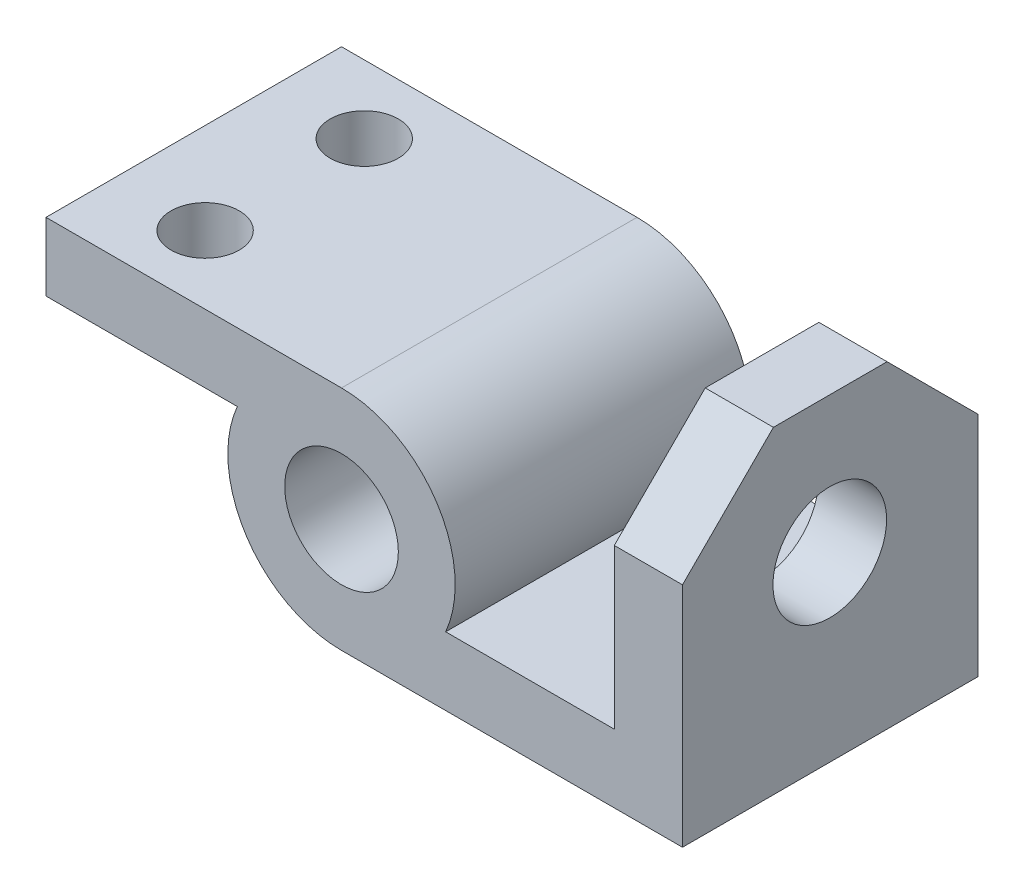
SolidWorks part; units mm, degrees
ref_plane "Front Plane" through (0, 0, 0) normal (0, 0, 1) x (1, 0, 0)
ref_plane "Top Plane" through (0, 0, 0) normal (0, 1, 0) x (1, 0, 0)
ref_plane "Right Plane" through (0, 0, 0) normal (1, 0, 0) x (0, 0, -1)
sketch "Sketch1" plane through (0, 0, 0) normal (0, 0, 1) x (1, 0, 0)
  line L0 (0, 1250) -> (-3250, 1250)
  line L1 (-3250, 1250) -> (-3250, 500)
  line L2 (-3250, 500) -> (-1145.6439, 500)
  line L3 (0, -1250) -> (3750, -1250)
  line L4 (3750, -1250) -> (3750, 2250)
  line L5 (3750, 2250) -> (3000, 2250)
  line L6 (3000, 2250) -> (3000, -500)
  line L7 (3000, -500) -> (1145.6439, -500)
  arc A0 (-1145.6439, 500) -> (0, -1250) centre (0, 0) ccw
  arc A1 (1145.6439, -500) -> (0, 1250) centre (0, 0) ccw
  dimension "D1" = 1250
  dimension "D2" = 3250
  dimension "D3" = 750
  dimension "D4" = 3500
  dimension "D5" = 750
  dimension "D6" = 3750
  dimension "D7" = 750
extrude "Boss-Extrude1" add sketch "Sketch1" along normal blind 3250
sketch "Sketch2" plane through (0, 0, 3250) normal (0, 0, 1) x (1, 0, 0)
  circle A0 centre (0, 0) radius 625
  dimension "D1" = 1250
extrude "Cut-Extrude1" cut sketch "Sketch2" against normal through all
sketch "Sketch3" plane through (0, 1250, 0) normal (0, 1, 0) x (1, 0, 0)
  line L0 (0, 0) -> (-3250, 0) construction
  line L1 (-3250, -3250) -> (-3250, 0) construction
  line L2 (0, -3250) -> (-3250, -3250) construction
  circle A0 centre (-2250, -750) radius 375
  circle A1 centre (-2250, -2500) radius 375
  point P6 (0, 0)
  dimension "D1" = 750
  dimension "D4" = 2
  dimension "D2" = 750
  dimension "D3" = 1000
  dimension "D5" = 750
extrude "Cut-Extrude2" cut sketch "Sketch3" against normal up to next contours A1 | A0
sketch "Sketch4" plane through (3750, 0, 0) normal (1, 0, 0) x (0, 0, -1)
  line L0 (-3250, -1250) -> (0, -1250) construction
  line L1 (0, -1250) -> (0, 2250) construction
  circle A0 centre (-1630, 750) radius 625
  dimension "D1" = 1250
  dimension "D2" = 2000
  dimension "D3" = 1630
extrude "Cut-Extrude3" cut sketch "Sketch4" against normal up to next
chamfer "Chamfer1" distance 1000 2 edges at (3375, 2250, 3250) (3375, 2250, 0)
